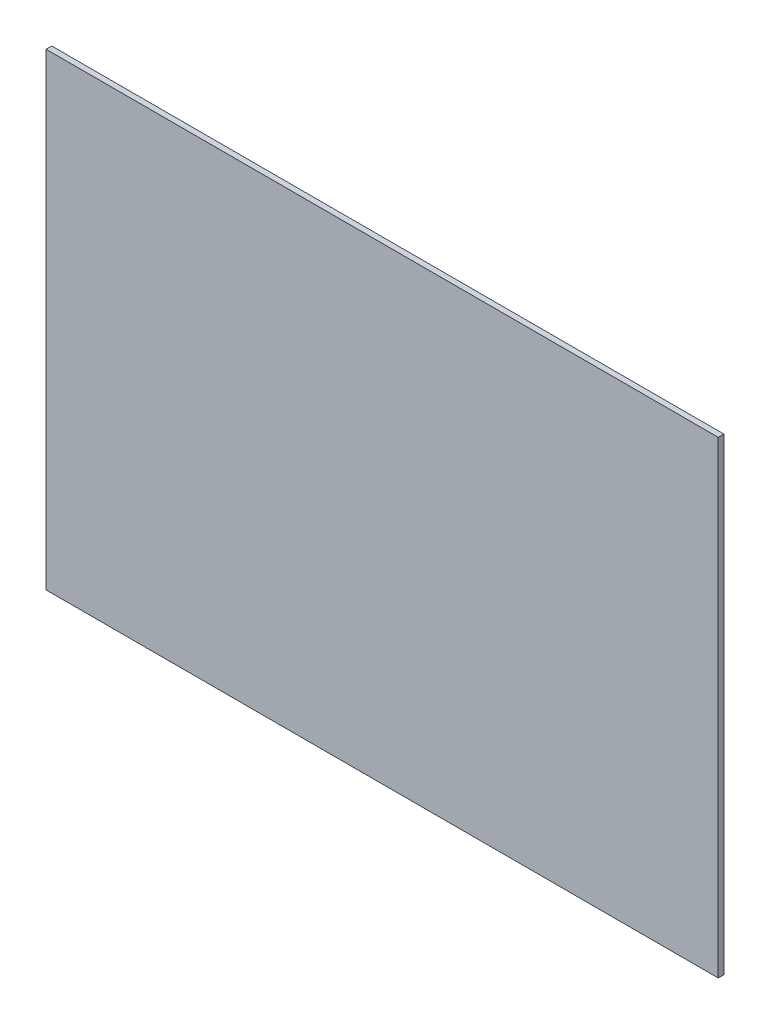
SolidWorks part; units mm, degrees
ref_plane "Plan de face" through (0, 0, 0) normal (0, 0, 1) x (1, 0, 0)
ref_plane "Plan de dessus" through (0, 0, 0) normal (0, 1, 0) x (1, 0, 0)
ref_plane "Plan de droite" through (0, 0, 0) normal (1, 0, 0) x (0, 0, -1)
sketch "Esquisse1" plane through (0, 0, 0) normal (0, 0, 1) x (1, 0, 0)
  line L1 (-168.2466, 86.5616) -> (187.7534, 86.5616)
  line L2 (-168.2466, 86.5616) -> (-168.2466, -161.4384)
  line L3 (-168.2466, -161.4384) -> (187.7534, -161.4384)
  line L4 (187.7534, 86.5616) -> (187.7534, -161.4384)
  dimension "D1" = 356
  dimension "D2" = 248
extrude "Boss.-Extru.1" add sketch "Esquisse1" along normal blind 3
